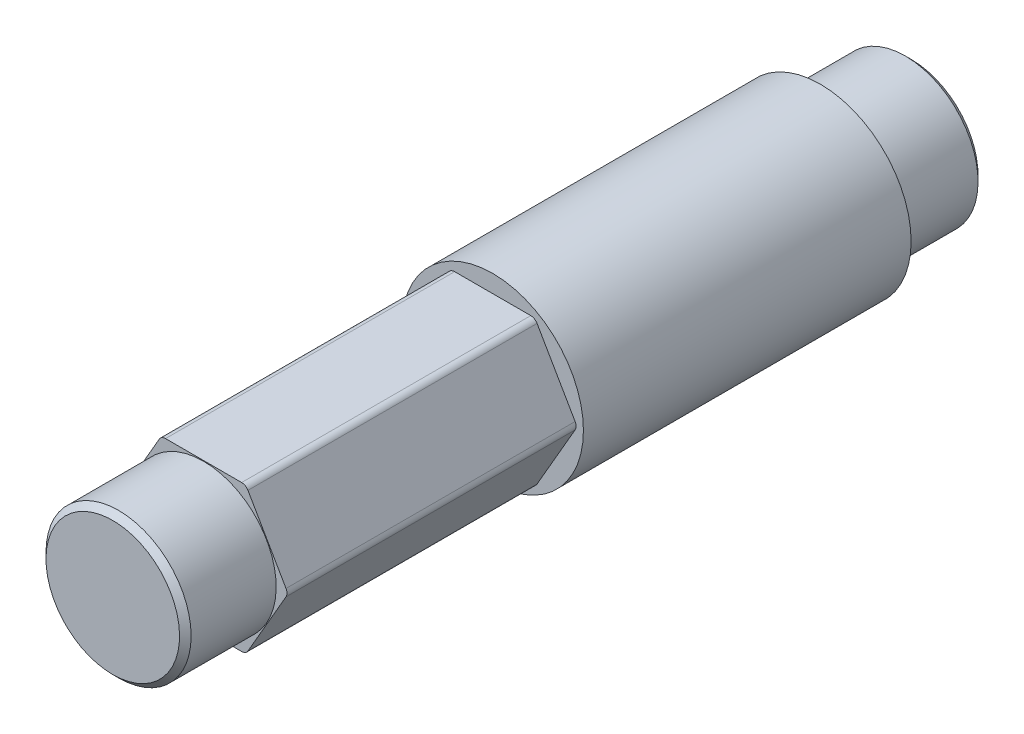
SolidWorks part; units mm, degrees
material "6061-T6 (SS)"
ref_plane "Front Plane" through (0, 0, 0) normal (0, 0, 1) x (1, 0, 0)
ref_plane "Top Plane" through (0, 0, 0) normal (0, 1, 0) x (1, 0, 0)
ref_plane "Right Plane" through (0, 0, 0) normal (1, 0, 0) x (0, 0, -1)
sketch "Sketch1" plane through (0, 0, 0) normal (1, 0, 0) x (0, 0, -1)
  line L0 (0, 0) -> (-16396.6126, 0) construction
  line L1 (0, 0) -> (0, 6.35)
  line L2 (0, 6.35) -> (7.9502, 6.35)
  line L3 (7.9502, 6.35) -> (7.9502, 7.62)
  line L4 (7.9502, 7.62) -> (33.2486, 7.62)
  line L5 (33.2486, 7.62) -> (33.2486, 7.9375)
  line L6 (33.2486, 7.9375) -> (61.9252, 7.9375)
  line L7 (61.9252, 7.9375) -> (61.9252, 6.35)
  line L8 (61.9252, 6.35) -> (69.8754, 6.35)
  line L9 (69.8754, 6.35) -> (69.8754, 0)
  line L10 (69.8754, 0) -> (0, 0)
  dimension "D1" = 7.9502
  dimension "D2" = 12.7
  dimension "D3" = 15.24
  dimension "D4" = 15.875
  dimension "D5" = 25.2984
  dimension "D6" = 28.6766
revolve "Revolve1" add sketch "Sketch1" angle 360 about L0
sketch "Sketch2" plane through (0, 0, -7.9502) normal (0, 0, 1) x (1, 0, 0)
  line L1 (3.697, 6.4033) -> (-3.697, 6.4033)
  line L2 (-3.697, 6.4033) -> (-7.3939, 0)
  line L3 (-7.3939, 0) -> (-3.697, -6.4033)
  line L4 (-3.697, -6.4033) -> (3.697, -6.4033)
  line L5 (3.697, -6.4033) -> (7.3939, 0)
  line L6 (7.3939, 0) -> (3.697, 6.4033)
  circle A0 centre (0, 0) radius 6.4033 construction
  dimension "D1" = 12.8067
extrude "Cut-Extrude1" cut sketch "Sketch2" against normal up to surface (25.2984 mm away) flip side to cut up to face at (0, 7.62, -33.2486)
chamfer "Chamfer1" distance 0.508 angle 45 2 edges at (0, 6.35, 0) (0, 6.35, -69.8754)
fillet "Fillet1" radius 0.635 6 edges at (-3.697, -6.4033, -20.5994) (3.697, -6.4033, -20.5994) (7.3939, 0, -20.5994) (3.697, 6.4033, -20.5994) (-3.697, 6.4033, -20.5994) (-7.3939, 0, -20.5994)
